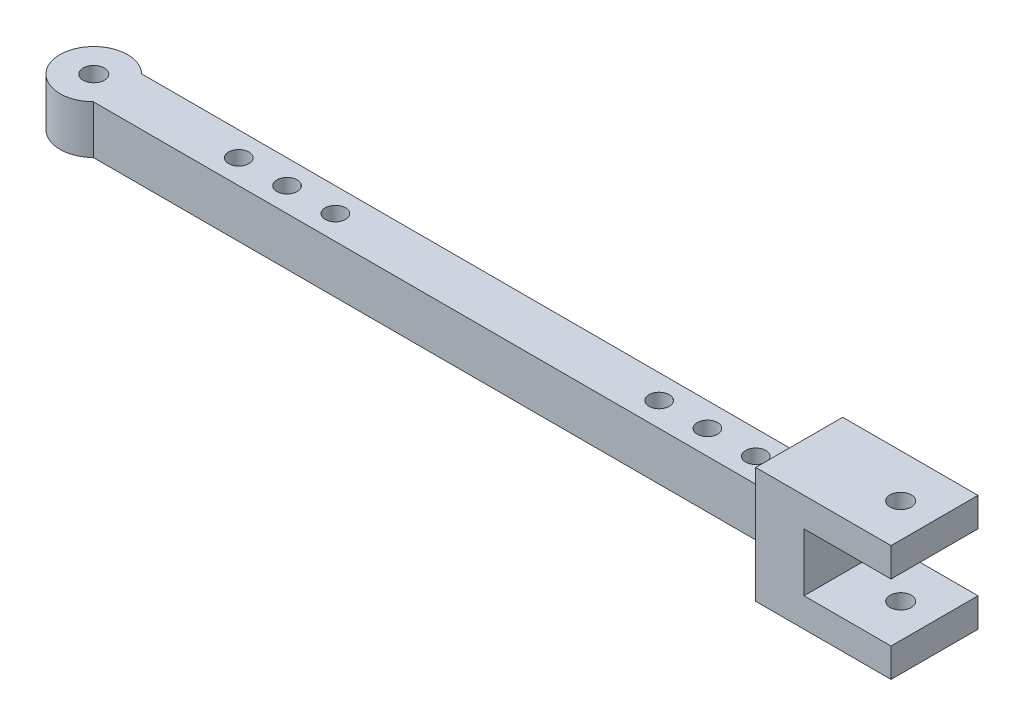
SolidWorks part; units mm, degrees
ref_plane "Front Plane" through (0, 0, 0) normal (0, 0, 1) x (1, 0, 0)
ref_plane "Top Plane" through (0, 0, 0) normal (0, 1, 0) x (1, 0, 0)
ref_plane "Right Plane" through (0, 0, 0) normal (1, 0, 0) x (0, 0, -1)
sketch "Sketch1" plane through (0, 0, 0) normal (0, 1, 0) x (1, 0, 0)
  line L1 (-40, 2.5) -> (40, 2.5)
  line L2 (-40, 2.5) -> (-40, -2.5)
  line L3 (-40, -2.5) -> (40, -2.5)
  line L4 (40, 2.5) -> (40, -2.5)
  line L5 (-40, 2.5) -> (40, -2.5) construction
  line L6 (-40, -2.5) -> (40, 2.5) construction
  point P0 (0, 0)
  dimension "D1" = 5
  dimension "D2" = 80
extrude "Boss-Extrude1" add sketch "Sketch1" along normal blind 5
sketch "Sketch7" plane through (0, 5, 0) normal (0, 1, 0) x (1, 0, 0)
  line L0 (40, -2.5) -> (40, 2.5) construction
  line L1 (33, 4.5) -> (47, 4.5)
  line L2 (33, 4.5) -> (33, -4.5)
  line L3 (33, -4.5) -> (47, -4.5)
  line L4 (47, 4.5) -> (47, -4.5)
  line L5 (33, 4.5) -> (47, -4.5) construction
  line L6 (33, -4.5) -> (47, 4.5) construction
  point P0 (40, 0)
  dimension "D1" = 9
  dimension "D2" = 14
extrude "Boss-Extrude4" add sketch "Sketch7" against normal blind 12 from offset 3.5
sketch "Sketch8" plane through (0, 5, 0) normal (0, 1, 0) x (1, 0, 0)
  line L0 (33, 2.5) -> (25, 2.5) construction
  line L1 (25, 2.5) -> (25, -2.5) construction
  line L2 (25, -2.5) -> (33, -2.5) construction
sketch "Sketch9" plane through (0, 8.5, 0) normal (0, 1, 0) x (1, 0, 0)
  line L0 (33, -4.5) -> (47, -4.5) construction
  line L1 (47, 4.5) -> (38, 4.5)
  line L2 (47, 4.5) -> (47, -4.5)
  line L3 (47, -4.5) -> (38, -4.5)
  line L4 (38, 4.5) -> (38, -4.5)
  dimension "D1" = 9
extrude "Cut-Extrude5" cut sketch "Sketch9" against normal blind 6 from offset 3 offset against normal yes
sketch "Sketch10" plane through (0, 8.5, 0) normal (0, 1, 0) x (1, 0, 0)
  line L0 (38, 4.5) -> (38, -4.5) construction
  line L1 (47, 4.5) -> (33, 4.5) construction
  line L2 (33, -4.5) -> (47, -4.5) construction
  line L3 (47, -4.5) -> (47, 4.5) construction
  dimension "D1" = 9
sketch "Sketch11" plane through (0, 8.5, 0) normal (0, 1, 0) x (1, 0, 0)
  line L0 (47, -4.5) -> (47, 4.5) construction
  circle A0 centre (43.5, 0) radius 1.1
  dimension "D1" = 3.5
  dimension "D2" = 2.2
extrude "Cut-Extrude6" cut sketch "Sketch11" against normal blind 12
sketch "Sketch15" plane through (0, 5, 0) normal (0, 1, 0) x (1, 0, 0)
  line L0 (-40, 2.5) -> (-40, -2.5) construction
  circle A0 centre (-40, 0) radius 1.1
sketch "Sketch16" plane through (0, 5, 0) normal (0, 1, 0) x (1, 0, 0)
  circle A0 centre (-40, 0) radius 3.5
extrude "Boss-Extrude7" add sketch "Sketch16" against normal blind 5 contours A0
extrude "Cut-Extrude9" cut sketch "Sketch15" against normal blind 5
sketch "Sketch17" plane through (0, 0, 0) normal (0, -1, 0) x (1, 0, 0)
  line L0 (-40, 0) -> (-40, -3.5) construction
  line L1 (43.5, 0) -> (43.5, -4.5) construction
  line L2 (47, -4.5) -> (33, -4.5) construction
  arc A0 (-37.5505, 2.5) -> (-37.5505, -2.5) centre (-40, 0) ccw construction
  circle A1 centre (-20, 0) radius 1.05
  circle A2 centre (23.5, 0) radius 1.05
  circle A3 centre (-25, 0) radius 1.05
  circle A4 centre (-15, 0) radius 1.05
  circle A5 centre (18.5, 0) radius 1.05
  circle A6 centre (28.5, 0) radius 1.05
  dimension "D1" = 20
  dimension "D2" = 20
  dimension "D3" = 5
  dimension "D4" = 5
  dimension "D5" = 5
  dimension "D6" = 5
extrude "Cut-Extrude10" cut sketch "Sketch17" against normal blind 5
